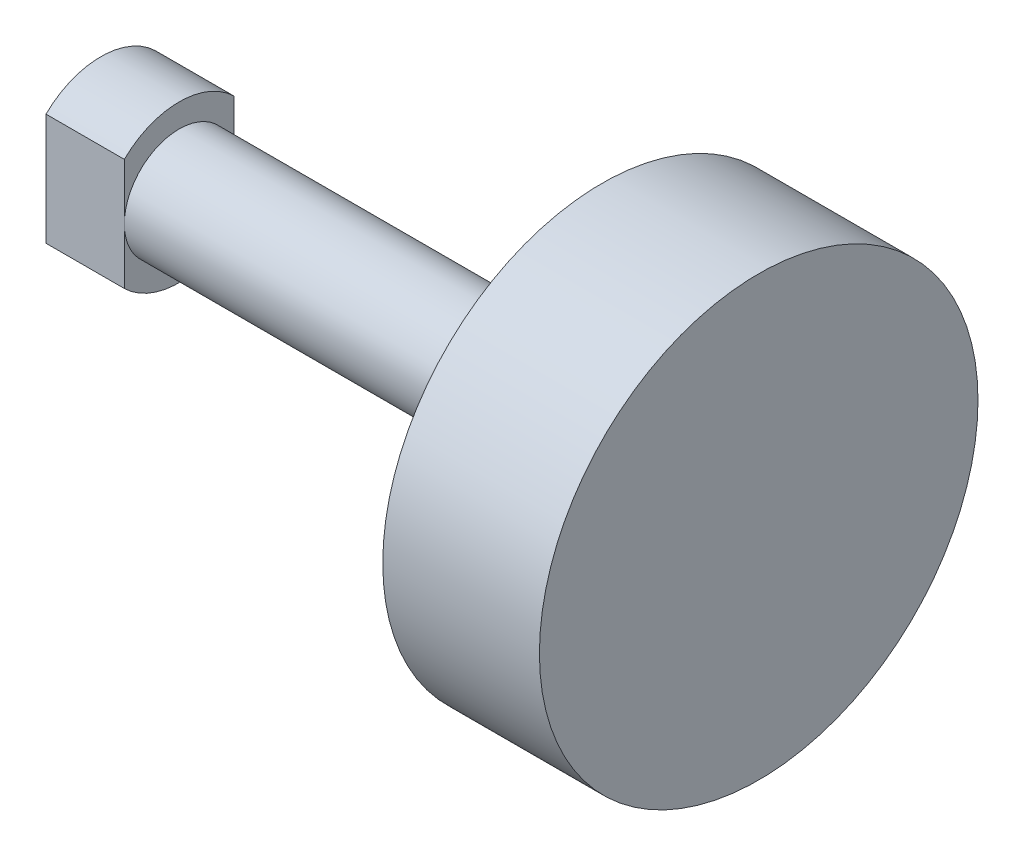
SolidWorks part; units mm, degrees
ref_plane "前视基准面" through (0, 0, 0) normal (0, 0, 1) x (1, 0, 0)
ref_plane "上视基准面" through (0, 0, 0) normal (0, 1, 0) x (1, 0, 0)
ref_plane "右视基准面" through (0, 0, 0) normal (1, 0, 0) x (0, 0, -1)
sketch "草图1" plane through (0, 0, 0) normal (0, 0, 1) x (1, 0, 0)
  line L0 (-40.913, 0) -> (35.7877, 0) construction
  line L1 (-19.8261, 0) -> (22.1739, 0)
  line L2 (-19.8261, 0) -> (-19.8261, 5)
  line L3 (-19.8261, 5) -> (-14.8261, 5)
  line L4 (-14.8261, 5) -> (-14.8261, 3.5)
  line L5 (-14.8261, 3.5) -> (20.1739, 3.5)
  line L6 (20.1739, 3.5) -> (20.1739, 12)
  line L7 (20.1739, 12) -> (12.1739, 12)
  line L8 (12.1739, 12) -> (12.1739, 14)
  line L9 (12.1739, 14) -> (22.1739, 14)
  line L10 (22.1739, 14) -> (22.1739, 0)
  dimension "D1" = 42
  dimension "D2" = 5
  dimension "D3" = 8.5
  dimension "D4" = 8
revolve "旋转1" add sketch "草图1" angle 360 about L0
sketch "草图7" plane through (12.1739, 0, 0) normal (-1, 0, 0) x (0, 0, 1)
  line L0 (-20.2606, 0) -> (17.6334, 0) construction
  line L2 (3.5, 12.7334) -> (18.3439, 12.7334)
  line L3 (3.5, 12.7334) -> (3.5, -14.6963)
  line L4 (3.5, -14.6963) -> (18.3439, -14.6963)
  line L5 (18.3439, 12.7334) -> (18.3439, -14.6963)
  dimension "D1" = 3.5
extrude "切除-拉伸1" cut sketch "草图7" along normal through all contours L3 L2 L5 L4
sketch "草图8" plane through (12.1739, 0, 0) normal (-1, 0, 0) x (0, 0, 1)
  line L0 (-19.5259, 0) -> (17.7447, 0) construction
  line L2 (-16.9032, 13.4939) -> (-3.5, 13.4939)
  line L3 (-16.9032, 13.4939) -> (-16.9032, -14.3589)
  line L4 (-16.9032, -14.3589) -> (-3.5, -14.3589)
  line L5 (-3.5, 13.4939) -> (-3.5, -14.3589)
  dimension "D1" = 3.5
extrude "切除-拉伸2" cut sketch "草图8" along normal through all contours L3 L2 L5 L4
sketch "草图3" plane through (-19.8261, 0, 0) normal (-1, 0, 0) x (0, 0, 1)
  line L0 (-6.9626, 0) -> (6.9554, 0) construction
  point P6 (0, 0)
  point P10 (-3.5, 0)
  point P13 (3.5, 0)
  point P14 (3.5, 3.5707)
  point P15 (0, 0)
  point P16 (0, 0)
  point P17 (3.5, 3.5707)
equation "\"D3@草图1\"=12-3.5"
